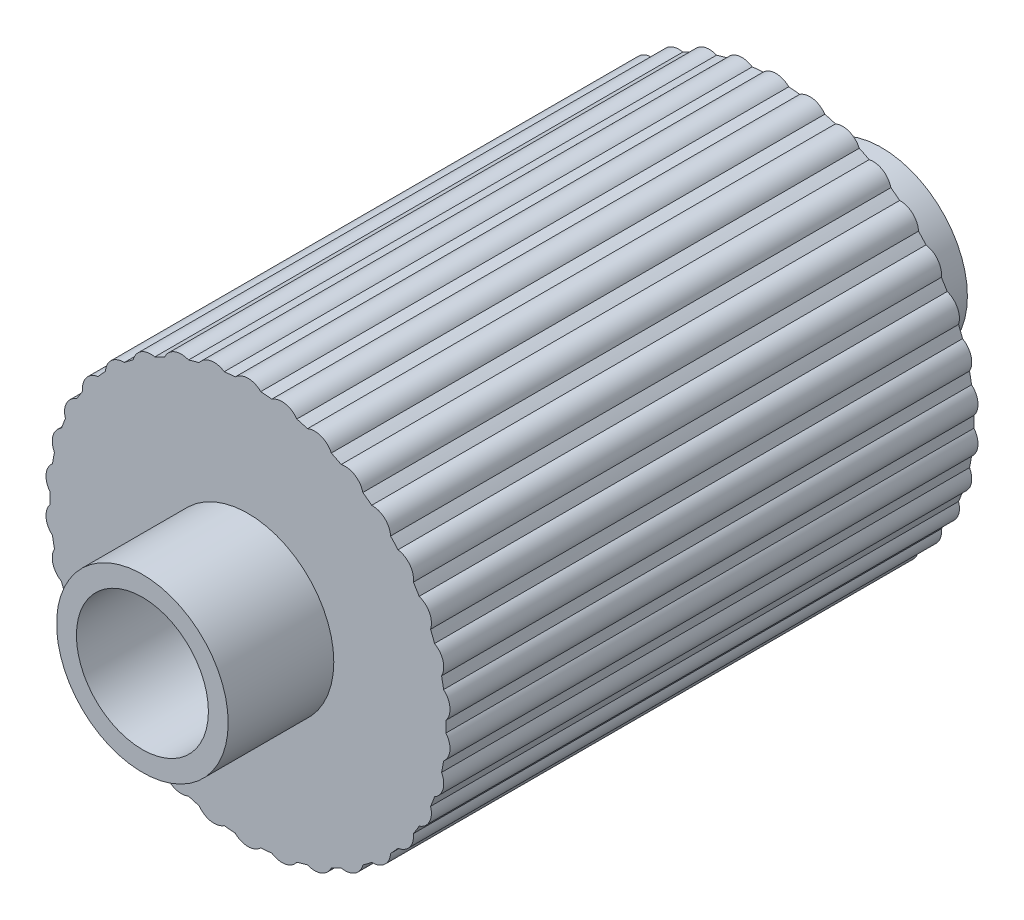
SolidWorks part; units mm, degrees
ref_plane "Front Plane" through (0, 0, 0) normal (0, 0, 1) x (1, 0, 0)
ref_plane "Top Plane" through (0, 0, 0) normal (0, 1, 0) x (1, 0, 0)
ref_plane "Right Plane" through (0, 0, 0) normal (1, 0, 0) x (0, 0, -1)
sketch "Sketch1" plane through (0, 0, 0) normal (0, 0, 1) x (1, 0, 0)
  line L0 (0, 15) -> (0, -15) construction
  line L1 (-15, 0) -> (15, 0) construction
  arc A0 (-3.7003, 14.5364) -> (-4.5064, 14.3071) centre (0, 0) ccw
  circle A1 centre (0, 0) radius 5
  arc A2 (0.9662, 14.9688) -> (-0.9662, 14.9688) centre (0, 13.984) ccw
  arc A3 (3.7003, 14.5364) -> (1.8008, 14.8915) centre (2.5696, 13.7459) ccw
  arc A4 (6.3083, 13.609) -> (4.5064, 14.3071) centre (5.0516, 13.0397) ccw
  arc A5 (8.7016, 12.2181) -> (7.0586, 13.2354) centre (7.3616, 11.8894) ccw
  arc A6 (10.7985, 10.4112) -> (9.3704, 11.713) centre (9.421, 10.3343) ccw
  arc A7 (12.5277, 8.2497) -> (11.3631, 9.7918) centre (11.1595, 8.4272) ccw
  arc A8 (13.8302, 5.8073) -> (12.9689, 7.5371) centre (12.518, 6.2332) ccw
  arc A9 (14.6618, 3.1671) -> (14.133, 5.0257) centre (13.4502, 3.8269) ccw
  arc A10 (14.9941, 0.4191) -> (14.8158, 2.3432) centre (13.9243, 1.2903) ccw
  arc A11 (14.8158, -2.3432) -> (14.9941, -0.4191) centre (13.9243, -1.2903) ccw
  arc A12 (14.133, -5.0257) -> (14.6618, -3.1671) centre (13.4502, -3.8269) ccw
  arc A13 (12.9689, -7.5371) -> (13.8302, -5.8073) centre (12.518, -6.2332) ccw
  arc A14 (11.3631, -9.7918) -> (12.5277, -8.2497) centre (11.1595, -8.4272) ccw
  arc A15 (9.3704, -11.713) -> (10.7985, -10.4112) centre (9.421, -10.3343) ccw
  arc A16 (7.0586, -13.2354) -> (8.7016, -12.2181) centre (7.3616, -11.8894) ccw
  arc A17 (4.5064, -14.3071) -> (6.3083, -13.609) centre (5.0516, -13.0397) ccw
  arc A18 (1.8008, -14.8915) -> (3.7003, -14.5364) centre (2.5696, -13.7459) ccw
  arc A19 (-0.9662, -14.9688) -> (0.9662, -14.9688) centre (0, -13.984) ccw
  arc A20 (-3.7003, -14.5364) -> (-1.8008, -14.8915) centre (-2.5696, -13.7459) ccw
  arc A21 (-6.3083, -13.609) -> (-4.5064, -14.3071) centre (-5.0516, -13.0397) ccw
  arc A22 (-8.7016, -12.2181) -> (-7.0586, -13.2354) centre (-7.3616, -11.8894) ccw
  arc A23 (-10.7985, -10.4112) -> (-9.3704, -11.713) centre (-9.421, -10.3343) ccw
  arc A24 (-12.5277, -8.2497) -> (-11.3631, -9.7918) centre (-11.1595, -8.4272) ccw
  arc A25 (-13.8302, -5.8073) -> (-12.9689, -7.5371) centre (-12.518, -6.2332) ccw
  arc A26 (-14.6618, -3.1671) -> (-14.133, -5.0257) centre (-13.4502, -3.8269) ccw
  arc A27 (-14.9941, -0.4191) -> (-14.8158, -2.3432) centre (-13.9243, -1.2903) ccw
  arc A28 (-14.8158, 2.3432) -> (-14.9941, 0.4191) centre (-13.9243, 1.2903) ccw
  arc A29 (-14.133, 5.0257) -> (-14.6618, 3.1671) centre (-13.4502, 3.8269) ccw
  arc A30 (-12.9689, 7.5371) -> (-13.8302, 5.8073) centre (-12.518, 6.2332) ccw
  arc A31 (-11.3631, 9.7918) -> (-12.5277, 8.2497) centre (-11.1595, 8.4272) ccw
  arc A32 (-9.3704, 11.713) -> (-10.7985, 10.4112) centre (-9.421, 10.3343) ccw
  arc A33 (-7.0586, 13.2354) -> (-8.7016, 12.2181) centre (-7.3616, 11.8894) ccw
  arc A34 (-4.5064, 14.3071) -> (-6.3083, 13.609) centre (-5.0516, 13.0397) ccw
  arc A35 (-1.8008, 14.8915) -> (-3.7003, 14.5364) centre (-2.5696, 13.7459) ccw
  arc A36 (-6.3083, 13.609) -> (-7.0586, 13.2354) centre (0, 0) ccw
  arc A37 (-8.7016, 12.2181) -> (-9.3704, 11.713) centre (0, 0) ccw
  arc A38 (-0.9662, 14.9688) -> (-1.8008, 14.8915) centre (0, 0) ccw
  arc A39 (1.8008, 14.8915) -> (0.9662, 14.9688) centre (0, 0) ccw
  arc A40 (4.5064, 14.3071) -> (3.7003, 14.5364) centre (0, 0) ccw
  arc A41 (7.0586, 13.2354) -> (6.3083, 13.609) centre (0, 0) ccw
  arc A42 (-10.7985, 10.4112) -> (-11.3631, 9.7918) centre (0, 0) ccw
  arc A43 (-12.5277, 8.2497) -> (-12.9689, 7.5371) centre (0, 0) ccw
  arc A44 (-13.8302, 5.8073) -> (-14.133, 5.0257) centre (0, 0) ccw
  arc A45 (-14.6618, 3.1671) -> (-14.8158, 2.3432) centre (0, 0) ccw
  arc A46 (-14.9941, 0.4191) -> (-14.9941, -0.4191) centre (0, 0) ccw
  arc A47 (-14.8158, -2.3432) -> (-14.6618, -3.1671) centre (0, 0) ccw
  arc A48 (-14.133, -5.0257) -> (-13.8302, -5.8073) centre (0, 0) ccw
  arc A49 (-12.9689, -7.5371) -> (-12.5277, -8.2497) centre (0, 0) ccw
  arc A50 (-11.3631, -9.7918) -> (-10.7985, -10.4112) centre (0, 0) ccw
  arc A51 (-9.3704, -11.713) -> (-8.7016, -12.2181) centre (0, 0) ccw
  arc A52 (-7.0586, -13.2354) -> (-6.3083, -13.609) centre (0, 0) ccw
  arc A53 (-4.5064, -14.3071) -> (-3.7003, -14.5364) centre (0, 0) ccw
  arc A54 (-1.8008, -14.8915) -> (-0.9662, -14.9688) centre (0, 0) ccw
  arc A55 (0.9662, -14.9688) -> (1.8008, -14.8915) centre (0, 0) ccw
  arc A56 (3.7003, -14.5364) -> (4.5064, -14.3071) centre (0, 0) ccw
  arc A57 (6.3083, -13.609) -> (7.0586, -13.2354) centre (0, 0) ccw
  arc A58 (8.7016, -12.2181) -> (9.3704, -11.713) centre (0, 0) ccw
  arc A59 (10.7985, -10.4112) -> (11.3631, -9.7918) centre (0, 0) ccw
  arc A60 (12.5277, -8.2497) -> (12.9689, -7.5371) centre (0, 0) ccw
  arc A61 (13.8302, -5.8073) -> (14.133, -5.0257) centre (0, 0) ccw
  arc A62 (14.6618, -3.1671) -> (14.8158, -2.3432) centre (0, 0) ccw
  arc A63 (14.9941, -0.4191) -> (14.9941, 0.4191) centre (0, 0) ccw
  arc A64 (14.8158, 2.3432) -> (14.6618, 3.1671) centre (0, 0) ccw
  arc A65 (14.133, 5.0257) -> (13.8302, 5.8073) centre (0, 0) ccw
  arc A66 (12.9689, 7.5371) -> (12.5277, 8.2497) centre (0, 0) ccw
  arc A67 (11.3631, 9.7918) -> (10.7985, 10.4112) centre (0, 0) ccw
  arc A68 (9.3704, 11.713) -> (8.7016, 12.2181) centre (0, 0) ccw
  point P112 (0, 0)
  dimension "D1" = 30
  dimension "D2" = 10
  dimension "D3" = 34
extrude "Boss-Extrude1" add sketch "Sketch1" along normal blind 40
sketch "Sketch2" plane through (0, 0, 40) normal (0, 0, 1) x (1, 0, 0)
  circle A0 centre (0, 0) radius 6.5
  dimension "D1" = 13
extrude "Boss-Extrude2" add sketch "Sketch2" along normal blind 8
sketch "Sketch3" plane through (0, 0, 48) normal (0, 0, 1) x (1, 0, 0)
  circle A0 centre (0, 0) radius 5
  dimension "D1" = 10
extrude "Cut-Extrude1" cut sketch "Sketch3" against normal through all and the other way through all
ref_plane "Plane1" through (0, 0, 20) normal (0, 0, -1) x (-1, 0, 0)
mirror "Mirror1" about plane through (0, 0, 20) normal (0, 0, -1) of "Boss-Extrude2"
sketch "Sketch4" plane through (0, 0, -8) normal (0, 0, -1) x (-1, 0, 0)
  circle A0 centre (0, 0) radius 5
  dimension "D1" = 10
extrude "Cut-Extrude2" cut sketch "Sketch4" against normal through all
